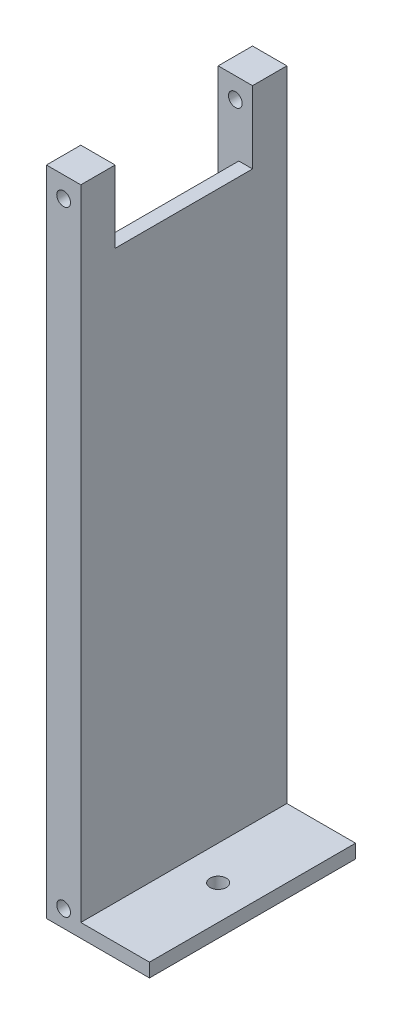
SolidWorks part; units mm, degrees
ref_plane "Front Plane" through (0, 0, 0) normal (0, 0, 1) x (1, 0, 0)
ref_plane "Top Plane" through (0, 0, 0) normal (0, 1, 0) x (1, 0, 0)
ref_plane "Right Plane" through (0, 0, 0) normal (1, 0, 0) x (0, 0, -1)
sketch "Sketch2" plane through (0, 0, 0) normal (1, 0, 0) x (0, 0, -1)
  line L1 (-15, -47.5) -> (15, -47.5)
  line L2 (-15, -47.5) -> (-15, 47.5)
  line L3 (-15, 47.5) -> (15, 47.5)
  line L4 (15, -47.5) -> (15, 47.5)
  line L5 (-15, -47.5) -> (15, 47.5) construction
  line L6 (-15, 47.5) -> (15, -47.5) construction
  point P0 (0, 0)
  dimension "D1" = 95
  dimension "D2" = 30
extrude "Boss-Extrude1" add sketch "Sketch2" along normal blind 5
hole_wizard "2mm Diameter Hole" positions "Sketch5" profile "Sketch4" hole size "3/32" standard "ANSI Inch" end condition through all
sketch "Sketch5" plane through (0, 0, -15) normal (0, 0, -1) x (-1, 0, 0)
  line L0 (-5, 47.5) -> (0, 47.5) construction
  line L1 (-5, -47.5) -> (-5, 47.5) construction
  point P0 (-2.5, 44.5)
  dimension "D1" = 3
  dimension "D2" = 2.5
sketch "Sketch4" plane through (2.5, 44.5, -15) normal (1, 0, 0) x (0, 1, 0)
  line L0 (0, 0) -> (0, 30)
  line L1 (0, 30) -> (1, 30)
  line L2 (1, 30) -> (1, 0)
  line L5 (1, 0) -> (0, 0)
  line L11 (0, -6.35) -> (0, 107.95) construction
  dimension "Thru Hole Dia." = 2
  dimension "Thru Hole Depth" = 30
sketch "Sketch6" plane through (5, 0, 0) normal (1, 0, 0) x (0, 0, -1)
  line L0 (-15, 47.5) -> (-15, -47.5) construction
  line L1 (15, -47.5) -> (-15, -47.5)
  line L2 (15, -47.5) -> (15, -45.5)
  line L3 (15, -45.5) -> (-15, -45.5)
  line L4 (-15, -47.5) -> (-15, -45.5)
  dimension "D1" = 2
extrude "Boss-Extrude2" add sketch "Sketch6" along normal blind 10
hole_wizard "3/32 (0.09375) Diameter Hole2" positions "Sketch8" profile "Sketch7" hole size "3/32" standard "ANSI Inch" end condition through all
sketch "Sketch8" plane through (0, -45.5, 0) normal (0, 1, 0) x (1, 0, 0)
  line L0 (15, 15) -> (5, 15) construction
  line L1 (15, 15) -> (15, -15) construction
  point P0 (10, 0)
  dimension "D1" = 15
  dimension "D2" = 5
sketch "Sketch7" plane through (10, -45.5, 0) normal (1, 0, 0) x (0, 0, 1)
  line L0 (0, 0) -> (0, 2)
  line L1 (0, 2) -> (1.1906, 2)
  line L2 (1.1906, 2) -> (1.1906, 0)
  line L5 (1.1906, 0) -> (0, 0)
  line L11 (0, -6.35) -> (0, 107.95) construction
  dimension "Thru Hole Dia." = 2.3812
  dimension "Thru Hole Depth" = 2
sketch "Sketch10" plane through (0, 0, 0) normal (-1, 0, 0) x (0, 0, 1)
  line L0 (-15, 47.5) -> (15, 47.5) construction
  line L1 (10, 47.5) -> (-10, 47.5)
  line L2 (10, 47.5) -> (10, 32.5)
  line L3 (10, 32.5) -> (-10, 32.5)
  line L4 (-10, 47.5) -> (-10, 32.5)
  line L5 (15, 47.5) -> (15, -47.5) construction
  line L6 (-15, -47.5) -> (-15, 47.5) construction
  dimension "D1" = 15
  dimension "D2" = 5
  dimension "D3" = 5
extrude "Cut-Extrude3" cut sketch "Sketch10" against normal blind 3
sketch "Sketch11" plane through (3, 0, 0) normal (-1, 0, 0) x (0, 0, 1)
  line L0 (-10, 43.634) -> (-10, 32.5) construction
  line L1 (10, 47.5) -> (-10, 47.5)
  line L2 (10, 47.5) -> (10, 37)
  line L3 (10, 37) -> (-10, 37)
  line L4 (-10, 47.5) -> (-10, 37)
  dimension "D1" = 10.5
extrude "Cut-Extrude4" cut sketch "Sketch11" against normal through all
hole_wizard "2mm Diameter Hole2" positions "Sketch13" profile "Sketch12" hole size "3/32" standard "ANSI Inch" end condition through all
sketch "Sketch13" plane through (0, 0, -15) normal (0, 0, -1) x (-1, 0, 0)
  line L0 (-15, -47.5) -> (0, -47.5) construction
  line L1 (0, -47.5) -> (0, 47.5) construction
  point P0 (-2.5, -45)
  point P9 (-2.475, -45)
  dimension "D1" = 2.5
  dimension "D2" = 2.5
sketch "Sketch12" plane through (2.5, -45, -15) normal (1, 0, 0) x (0, 1, 0)
  line L0 (0, 0) -> (0, 30.0001)
  line L1 (0, 30.0001) -> (1, 30.0001)
  line L2 (1, 30.0001) -> (1, 0)
  line L5 (1, 0) -> (0, 0)
  line L11 (0, -6.35) -> (0, 107.95) construction
  dimension "Thru Hole Dia." = 2
  dimension "Thru Hole Depth" = 30.0001
